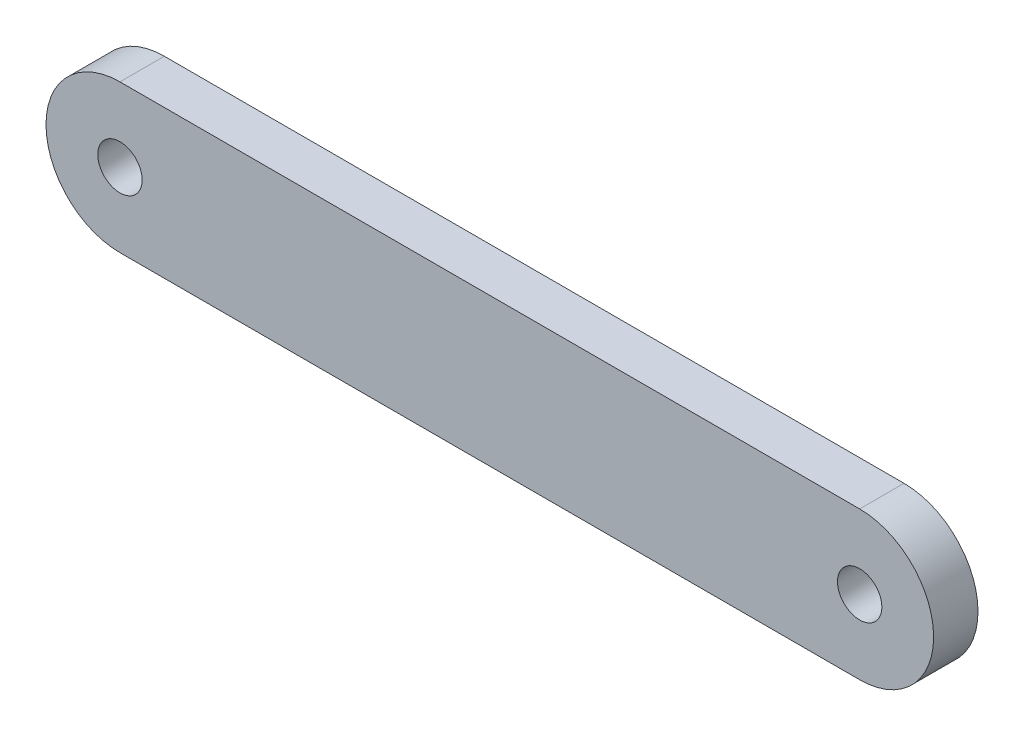
SolidWorks part; units mm, degrees
material "Acrylic (Medium-high impact)"
ref_plane "Front Plane" through (0, 0, 0) normal (0, 0, 1) x (1, 0, 0)
ref_plane "Top Plane" through (0, 0, 0) normal (0, 1, 0) x (1, 0, 0)
ref_plane "Right Plane" through (0, 0, 0) normal (1, 0, 0) x (0, 0, -1)
sketch "Sketch1" plane through (0, 0, 0) normal (0, 0, 1) x (1, 0, 0)
  line L0 (0, 0) -> (50, 0) construction
  line L1 (0, 5) -> (50, 5)
  line L2 (0, -5) -> (50, -5)
  arc A0 (0, 5) -> (0, -5) centre (0, 0) ccw
  arc A1 (50, -5) -> (50, 5) centre (50, 0) ccw
  circle A2 centre (0, 0) radius 1.5
  circle A3 centre (50, 0) radius 1.5
  point P3 (25, 0)
  dimension "D3" = 3
  dimension "D4" = 3
  dimension "D1" = 50
  dimension "D2" = 10
extrude "Boss-Extrude1" add sketch "Sketch1" along normal blind 3
